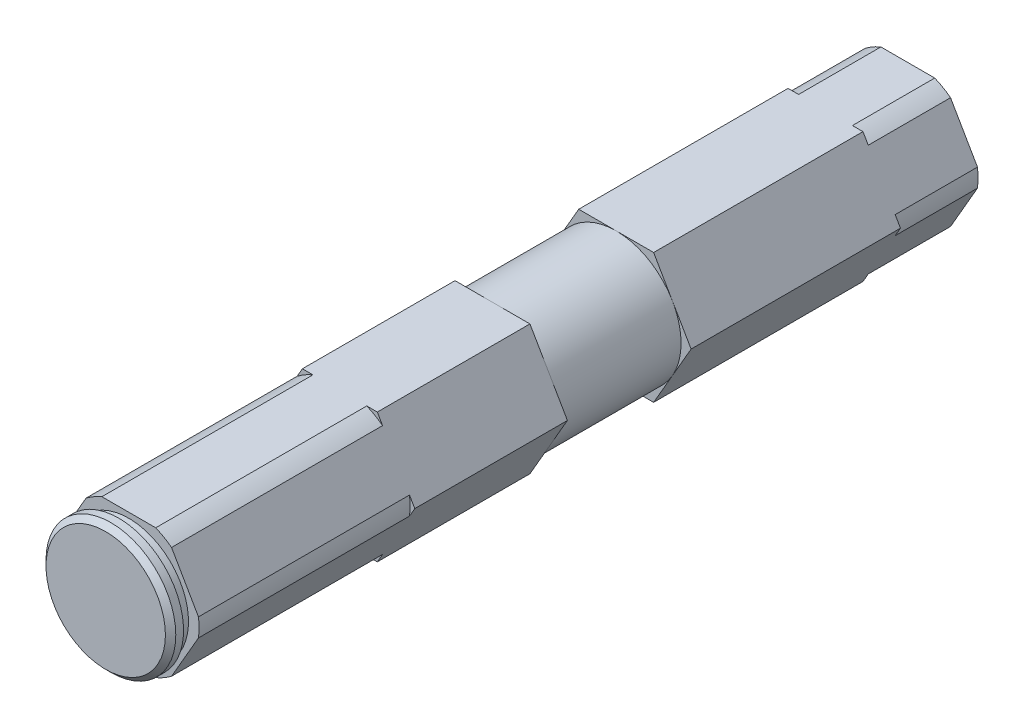
SolidWorks part; units mm, degrees
material "6061-T6 (SS)"
ref_plane "Front Plane" through (0, 0, 0) normal (0, 0, 1) x (1, 0, 0)
ref_plane "Top Plane" through (0, 0, 0) normal (0, 1, 0) x (1, 0, 0)
ref_plane "Right Plane" through (0, 0, 0) normal (1, 0, 0) x (0, 0, -1)
sketch "Sketch1" plane through (0, 0, 0) normal (1, 0, 0) x (0, 0, -1)
  line L0 (0, 0) -> (-24340.3872, 0) construction
  line L1 (0, 0) -> (0, 6.35)
  line L2 (0, 6.35) -> (1.27, 6.35)
  line L3 (1.27, 6.35) -> (1.27, 5.842)
  line L4 (1.27, 5.842) -> (2.2606, 5.842)
  line L5 (2.2606, 5.842) -> (2.2606, 6.875)
  line L6 (2.2606, 6.875) -> (22.9108, 6.875)
  line L7 (39.243, 6.8707) -> (39.243, 0) construction
  line L8 (0, 0) -> (78.486, 0)
  line L14 (78.486, 0) -> (78.486, 6.875)
  line L18 (49.9491, 7.9375) -> (70.4342, 7.9375)
  line L19 (37.846, 6.35) -> (49.9491, 6.35)
  line L20 (49.9491, 6.35) -> (49.9491, 7.9375)
  line L21 (37.846, 6.875) -> (37.846, 6.35)
  line L26 (70.4342, 7.9375) -> (70.4342, 6.875)
  line L27 (70.4342, 6.875) -> (78.486, 6.875)
  line L28 (22.9108, 7.9375) -> (37.846, 7.9375)
  line L29 (22.9108, 7.9375) -> (22.9108, 6.875)
  line L30 (37.846, 7.9375) -> (37.846, 6.875)
  point P14 (39.243, 0)
  dimension "D2" = 12.7
  dimension "D3" = 1.27
  dimension "D4" = 0.9906
  dimension "D5" = 11.684
  dimension "D6" = 47.5234
  dimension "D7" = 14.9352
  dimension "D8" = 15.875
  dimension "D9" = 8.0518
  dimension "D10" = 13.75
  dimension "D11" = 28.5369
  dimension "D12" = 12.7
  dimension "D14" = 22.9108
revolve "Revolve1" add sketch "Sketch1" angle 360 about L0
sketch "Sketch2" plane through (0, 0, -2.2606) normal (0, 0, 1) x (1, 0, 0)
  line L1 (3.6662, 6.35) -> (-3.6662, 6.35)
  line L2 (-3.6662, 6.35) -> (-7.3323, 0)
  line L3 (-7.3323, 0) -> (-3.6662, -6.35)
  line L4 (-3.6662, -6.35) -> (3.6662, -6.35)
  line L5 (3.6662, -6.35) -> (7.3323, 0)
  line L6 (7.3323, 0) -> (3.6662, 6.35)
  circle A0 centre (0, 0) radius 6.35 construction
  dimension "D1" = 12.7
extrude "Cut-Extrude1" cut sketch "Sketch2" against normal through all flip side to cut
chamfer "Chamfer1" distance 0.508 angle 45 1 edges at (-6.35, 0, 0)
